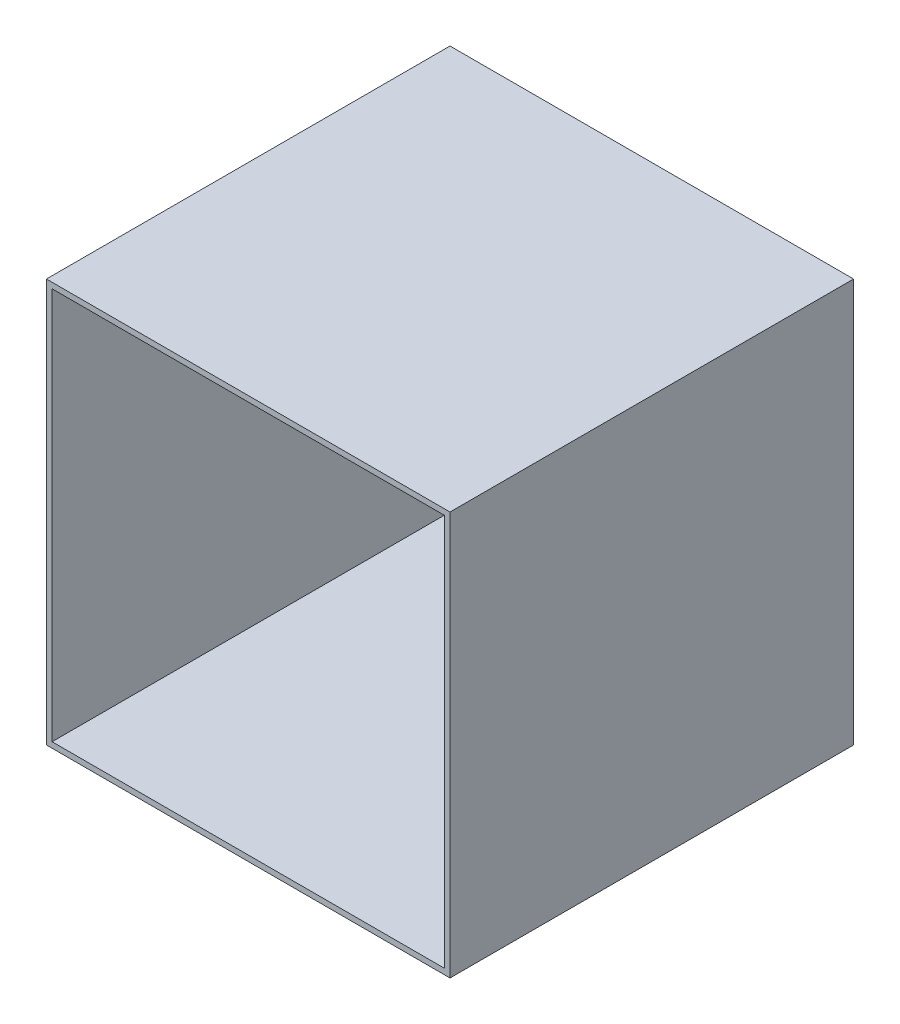
SolidWorks part; units mm, degrees
ref_plane "Front Plane" through (0, 0, 0) normal (0, 0, 1) x (1, 0, 0)
ref_plane "Top Plane" through (0, 0, 0) normal (0, 1, 0) x (1, 0, 0)
ref_plane "Right Plane" through (0, 0, 0) normal (1, 0, 0) x (0, 0, -1)
sketch "Sketch1" plane through (0, 0, 0) normal (0, 0, 1) x (1, 0, 0)
  line L1 (-12.15, 12.15) -> (12.15, 12.15)
  line L2 (-12.15, 12.15) -> (-12.15, -12.15)
  line L3 (-12.15, -12.15) -> (12.15, -12.15)
  line L4 (12.15, 12.15) -> (12.15, -12.15)
  line L5 (-12.15, 12.15) -> (12.15, -12.15) construction
  line L6 (-12.15, -12.15) -> (12.15, 12.15) construction
  line L7 (-12.5, 12.5) -> (12.5, 12.5)
  line L8 (-12.5, 12.5) -> (-12.5, -12.5)
  line L9 (-12.5, -12.5) -> (12.5, -12.5)
  line L10 (12.5, 12.5) -> (12.5, -12.5)
  line L11 (-12.5, 12.5) -> (12.5, -12.5) construction
  line L12 (-12.5, -12.5) -> (12.5, 12.5) construction
  point P0 (0, 0)
  point P7 (0, 0)
  dimension "D1" = 0.35
  dimension "D2" = 0.35
  dimension "D3" = 25
extrude "Boss-Extrude1" add sketch "Sketch1" along normal blind 25
fillet "Fillet1" [suppressed] radius 2
fillet "Fillet2" [suppressed] radius 2.4
